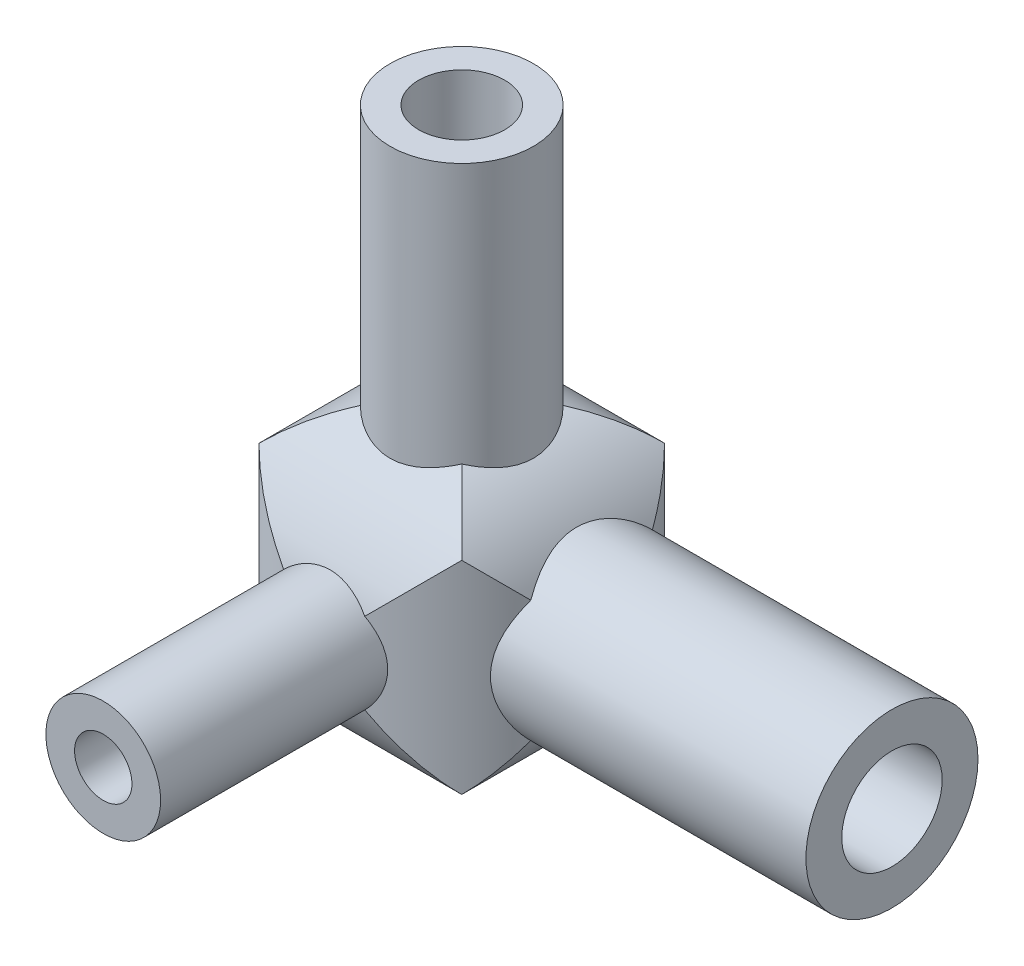
SolidWorks part; units mm, degrees
ref_plane "前视基准面" through (0, 0, 0) normal (0, 0, 1) x (1, 0, 0)
ref_plane "上视基准面" through (0, 0, 0) normal (0, 1, 0) x (1, 0, 0)
ref_plane "右视基准面" through (0, 0, 0) normal (1, 0, 0) x (0, 0, -1)
ref_plane "基准面1" through (0, 0, -20) normal (0, 0, 1) x (1, 0, 0)
sketch "草图1" plane through (0, 0, -20) normal (0, 0, 1) x (1, 0, 0)
  circle A0 centre (0, 0) radius 20
extrude "凸台-拉伸1" add sketch "草图1" along normal blind 40
ref_plane "基准面2" through (-20, 0, 0) normal (1, 0, 0) x (0, 0, -1)
sketch "草图2" plane through (-20, 0, 0) normal (1, 0, 0) x (0, 0, -1)
  line L0 (20.0005, -20.0005) -> (-20.0005, -20.0005)
  line L1 (-20.0005, -20.0005) -> (-20.0005, 20.0005)
  line L2 (-20.0005, 20.0005) -> (20.0005, 20.0005)
  line L3 (20.0005, 20.0005) -> (20.0005, -20.0005)
  circle A0 centre (0, 0) radius 20
extrude "切除-拉伸1" cut sketch "草图2" against normal mid plane 40
sketch "草图3" plane through (0, 0, 0) normal (1, 0, 0) x (0, 0, -1)
  line L0 (20.0005, -20.0005) -> (-20.0005, -20.0005)
  line L1 (-20.0005, -20.0005) -> (-20.0005, 20.0005)
  line L2 (-20.0005, 20.0005) -> (20.0005, 20.0005)
  line L3 (20.0005, 20.0005) -> (20.0005, -20.0005)
  circle A0 centre (0, 0) radius 20
extrude "切除-拉伸2" cut sketch "草图3" against normal mid plane 40
ref_plane "基准面3" through (0, -20, 0) normal (0, 1, 0) x (1, 0, 0)
sketch "草图16" plane through (0, 0, 0) normal (0, 1, 0) x (1, 0, 0)
  line L0 (-20.0005, 20.0005) -> (20.0005, 20.0005)
  line L1 (20.0005, 20.0005) -> (20.0005, -20.0005)
  line L2 (20.0005, -20.0005) -> (-20.0005, -20.0005)
  line L3 (-20.0005, -20.0005) -> (-20.0005, 20.0005)
  circle A0 centre (0, 0) radius 20
extrude "切除-拉伸5" cut sketch "草图16" against normal mid plane 40
sketch3d "3D草图3"
  line L0 (0, 0, 0) -> (60, 0, 0)
sweep "扫描6" add path "3D草图3" circular profile diameter 24 parameters "D3"=24
sketch3d "3D草图4"
  line L0 (0, 0, 0) -> (0, 55, 0)
sweep "扫描8" add path "3D草图4" circular profile diameter 20 parameters "D3"=20
sketch3d "3D草图5"
  line L0 (0, 0, 0) -> (0, 0, 50)
sweep "扫描10" add path "3D草图5" circular profile diameter 16 parameters "D3"=16
sketch3d "3D草图6"
  line L0 (0, 0, 0) -> (-16.6667, -16.6667, -16.6667)
sweep "扫描12" add path "3D草图6" circular profile diameter 12 parameters "D3"=12
sketch3d "3D草图7"
  line L0 (-11.547, -11.547, -11.547) -> (-28.8675, -28.8675, -28.8675)
sweep "扫描14" add path "3D草图7" circular profile diameter 12 parameters "D3"=12
ref_plane "基准面4" through (0, -28.8675, 0) normal (0, 1, 0) x (1, 0, 0)
sketch "草图22" plane through (0, -28.8675, 0) normal (0, 1, 0) x (1, 0, 0)
  line L0 (-34.8675, 28.8675) -> (-22.8675, 28.8675) construction
  line L1 (-22.8675, 28.8675) -> (-34.8675, 28.8675)
  arc A0 (-34.8675, 28.8675) -> (-22.8675, 28.8675) centre (-28.8675, 28.8675) cw
revolve "旋转1" add sketch "草图22" angle 360 about L0
sketch3d "3D草图8"
  line L0 (61, 0, 0) -> (-5, 0, 0)
sweep "切除-扫描2" cut path "3D草图8" circular profile diameter 14 parameters "D3"=14
sketch3d "3D草图9"
  line L0 (0, 56, 0) -> (0, -5, 0)
sweep "切除-扫描4" cut path "3D草图9" circular profile diameter 12 parameters "D3"=12
sketch3d "3D草图10"
  line L0 (0, 0, 51) -> (0, 0, -5)
sweep "切除-扫描6" cut path "3D草图10" circular profile diameter 8 parameters "D3"=8
